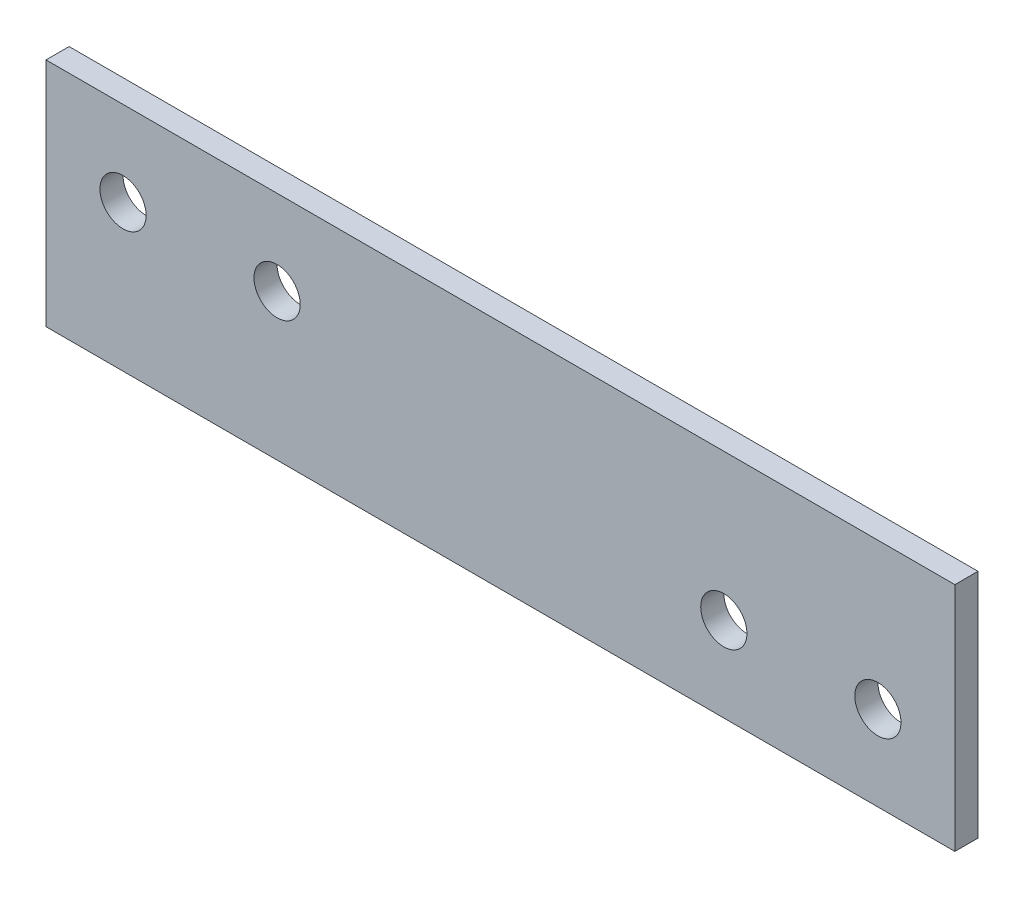
SolidWorks part; units mm, degrees
ref_plane "Plan de face" through (0, 0, 0) normal (0, 0, 1) x (1, 0, 0)
ref_plane "Plan de dessus" through (0, 0, 0) normal (0, 1, 0) x (1, 0, 0)
ref_plane "Plan de droite" through (0, 0, 0) normal (1, 0, 0) x (0, 0, -1)
sketch "Esquisse1" plane through (0, 0, 0) normal (0, 0, 1) x (1, 0, 0)
  line L1 (-22.2042, 12.0449) -> (36.7958, 12.0449)
  line L2 (-22.2042, 12.0449) -> (-22.2042, -2.9551)
  line L3 (-22.2042, -2.9551) -> (36.7958, -2.9551)
  line L4 (36.7958, 12.0449) -> (36.7958, -2.9551)
  dimension "D1" = 59
  dimension "D2" = 15
extrude "Extrusion1" add sketch "Esquisse1" along normal blind 1.5
sketch "Esquisse2" plane through (0, 0, 0) normal (0, 0, -1) x (-1, 0, 0)
  line L0 (-31.7958, 2.5449) -> (-21.7958, 2.5449) construction
  line L1 (-36.7958, -2.9551) -> (-36.7958, 12.0449) construction
  line L2 (22.2042, 12.0449) -> (22.2042, -2.9551) construction
  line L3 (7.2042, 6.5449) -> (17.2042, 6.5449) construction
  line L4 (-36.7958, 12.0449) -> (22.2042, 12.0449) construction
  line L5 (22.2042, -2.9551) -> (-36.7958, -2.9551) construction
  circle A0 centre (-31.7958, 2.5449) radius 1.5
  circle A1 centre (-21.7958, 2.5449) radius 1.5
  circle A2 centre (17.2042, 6.5449) radius 1.5
  circle A3 centre (7.2042, 6.5449) radius 1.5
  dimension "D1" = 5
  dimension "D2" = 10
  dimension "D3" = 5
  dimension "D4" = 10
  dimension "D5" = 9.5
  dimension "D6" = 9.5
extrude "Extrusion2" cut sketch "Esquisse2" against normal blind 1.5
